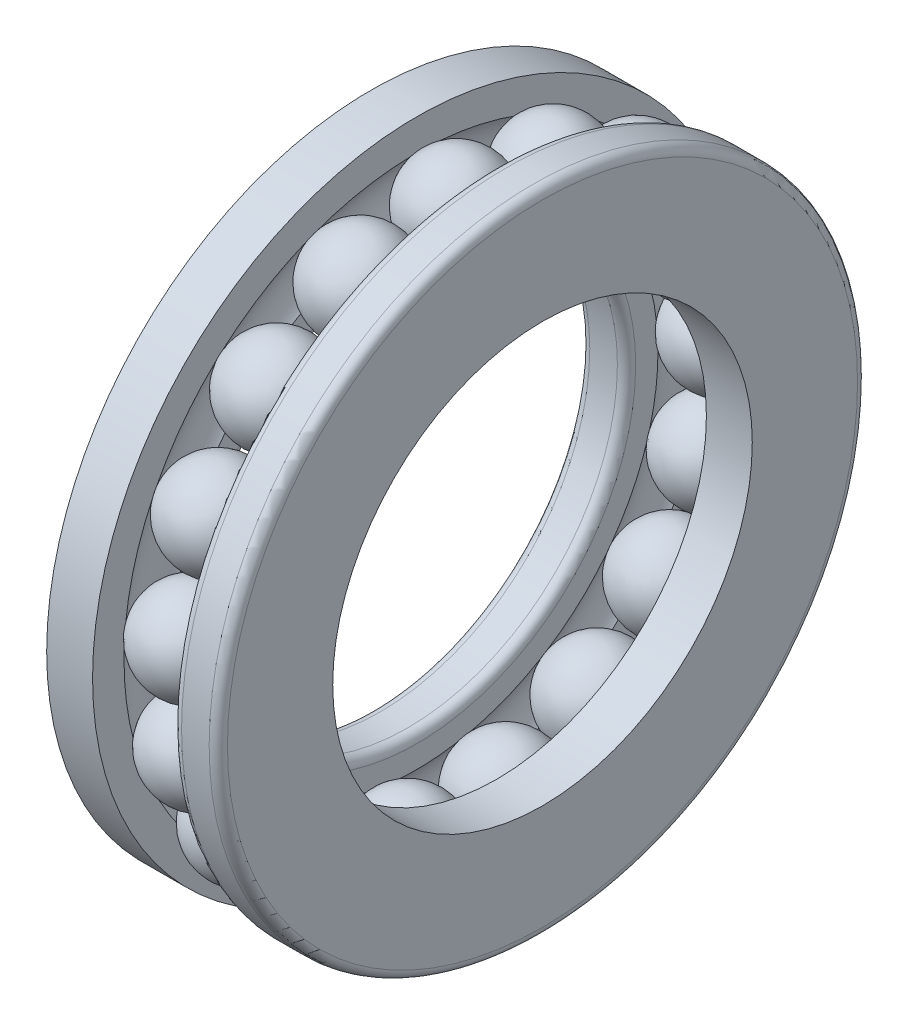
SolidWorks part; units mm, degrees
ref_plane "Plane1" through (0, 0, 0) normal (0, 0, 1) x (1, 0, 0)
ref_plane "Plane2" through (0, 0, 0) normal (0, 1, 0) x (1, 0, 0)
ref_plane "Plane3" through (0, 0, 0) normal (1, 0, 0) x (0, 0, -1)
sketch "Clipboard" plane through (0, 0, 0) normal (0, 0, 1) x (1, 0, 0)
  line L0 (-10, 0) -> (10, 0) construction
  line L1 (0, 0) -> (21.3836, -6.5376)
  line L2 (0, 0) -> (27.3662, 35.0271)
  line L3 (0, 0) -> (13.7666, -17.6205)
  line L4 (0, 0) -> (-22.3471, -0.7804)
  dimension "BallCLRad" = 44.45
  dimension "Count" = 52
  dimension "Show_count" = 52
  dimension "Max_count" = 17
  dimension "Min_count" = 2
sketch "InnRacSke" plane through (0, 0, 0) normal (0, 0, 1) x (1, 0, 0)
  line L0 (-6.6469, 40.1581) -> (-6.6469, 34.925)
  line L1 (-6.6469, 34.925) -> (-14.2875, 34.925)
  line L2 (-14.2875, 34.925) -> (-14.2875, 53.975)
  line L3 (-14.2875, 53.975) -> (-6.6469, 53.975)
  line L4 (-6.6469, 53.975) -> (-6.6469, 48.7419)
  line L5 (-34.9219, 0) -> (34.9219, 0) construction
  line L6 (0, 0) -> (0, 25.4) construction
  arc A2 (-6.6469, 48.7419) -> (-6.6469, 40.1581) centre (0, 44.45) ccw
  dimension "BallCLRad" = 44.45
  dimension "Ball_diameter" = 15.8242
  dimension "ID" = 69.85
  dimension "OD" = 107.95
  dimension "Width" = 28.575
  dimension "gap" = 13.2937
revolve "Race" add sketch "InnRacSke" angle 360 about L5
ref_axis "Axis1" through (-50, 0, 0) along (1, 0, 0)
sketch "BalDetSke" plane through (0, 0, 0) normal (0, 0, 1) x (1, 0, 0)
  line L0 (-7.9375, 44.45) -> (7.9375, 44.45)
  line L1 (-14.5732, 44.45) -> (14.5732, 44.45) construction
  arc A0 (7.9375, 44.45) -> (-7.9375, 44.45) centre (0, 44.45) cw
  dimension "BallCLRad" = 44.45
  dimension "Ball_diameter" = 15.875
revolve "BallDetailed" add sketch "BalDetSke" angle 360 about L1
sketch "BalSimSke" plane through (0, 0, 0) normal (0, 0, 1) x (1, 0, 0)
  line L0 (-25.4, 0) -> (25.4, 0) construction
  circle A0 centre (0, 44.45) radius 7.9375
  dimension "BallCLRad" = 44.45
  dimension "Ball_diameter" = 15.875
revolve "BallsSimplified" [suppressed] add sketch "BalSimSke" angle 360 about L0
mirror "Mirror1" about plane through (0, 0, 0) normal (1, 0, 0) of "Race"
fillet "Fillet" radius 1.524 4 edges at (6.6469, 0, -53.975) (14.2875, 0, -53.975) (-6.6469, 0, -34.925) (-14.2875, 0, -34.925)
pattern_circular "BallsDetailed" count 17 every 21.176 about axis through (-50, 0, 0) along (1, 0, 0) of "BallDetailed"
sketch "CagSpiSke" plane through (0, 0, 0) normal (0, 0, 1) x (1, 0, 0)
  line L0 (1.9844, 35.7188) -> (1.9844, 53.1812)
  line L1 (1.9844, 53.1812) -> (-1.9844, 53.1812)
  line L2 (-1.9844, 35.7188) -> (-1.9844, 53.1812)
  line L3 (-1.9844, 35.7188) -> (1.9844, 35.7188)
  line L4 (-34.925, 0) -> (34.925, 0) construction
  line L5 (0, 0) -> (0, 76.2) construction
  dimension "ID" = 71.4375
  dimension "OD" = 106.3625
  dimension "Thickness" = 3.9687
revolve "CageSpine" [suppressed] add sketch "CagSpiSke" angle 360 about L4
equation "\"BallCLRad@Clipboard\" =  ( \"OD@InnRacSke\" + \"ID@InnRacSke\" )  / 4"
equation "\"BallCLRad@BalSimSke\" = \"BallCLRad@Clipboard\""
equation "\"BallCLRad@BalDetSke\" = \"BallCLRad@Clipboard\""
equation "\"BallCLRad@InnRacSke\" = \"BallCLRad@Clipboard\""
equation "\"Ball_diameter@InnRacSke\" = \"Ball_diameter@BalDetSke\" - 0.002"
equation "\"Ball_diameter@BalSimSke\" = \"Ball_diameter@BalDetSke\""
equation "\"Max_count@Clipboard\" = int( 3.14159265 / atn(( \"Ball_diameter@BalDetSke\" / 2) / sqr( \"BallCLRad@Clipboard\"  *  \"BallCLRad@Clipboard\" - ( \"Ball_diameter@BalDetSke\" / 2) *  ( \"Ball_diameter@BalDetSke\" / 2))))"
equation "\"Max_count@Clipboard\" = ((sgn( \"Max_count@Clipboard\" - \"Count@Clipboard\" )-1)*( \"Max_count@Clipboard\" - \"Count@Clipboard\" ))/-2+ \"Count@Clipboard\""
equation "\"Count@BallsDetailed\" = int( \"Show_count@Clipboard\" ) "
equation "\"Count@BallsDetailed\" = ((sgn( \"Count@BallsDetailed\" - \"Max_count@Clipboard\" )-1)*( \"Count@BallsDetailed\" - \"Max_count@Clipboard\" ))/-2+ \"Max_count@Clipboard\""
equation "\"Count@BallsDetailed\" = ((sgn( \"Count@BallsDetailed\" - \"Min_count@Clipboard\" )+1)*( \"Count@BallsDetailed\" - \"Min_count@Clipboard\"))/2 +\"Min_count@Clipboard\""
equation "\"Angle@BallsDetailed\" = 360.0 / \"Max_count@Clipboard\""
equation "\"Angle@CageSpine\" =  \"Angle@BallsDetailed\" * ( \"Count@BallsDetailed\" -1 + int( \"Count@BallsDetailed\" / \"Max_count@Clipboard\" ) )  + 0.001 -  int( \"Count@BallsDetailed\" / \"Max_count@Clipboard\" ) * 0.001"
equation "\"Angle@CageSpine\" =  \"Angle@CageSpine\" * int( \"Min_count@Clipboard\" / 2) + int(1 / \"Min_count@Clipboard\")  * 0.001"
equation "\"Thickness@CagSpiSke\" =  \"Ball_diameter@BalDetSke\" * 0.25"
equation "\"OD@CagSpiSke\" = ( \"OD@InnRacSke\" + ( \"BallCLRad@Clipboard\" * 2 + \"Ball_diameter@BalDetSke\" )) / 2"
equation "\"ID@CagSpiSke\" = ( \"ID@InnRacSke\" + ( \"BallCLRad@Clipboard\" * 2 - \"Ball_diameter@BalDetSke\" )) / 2"
